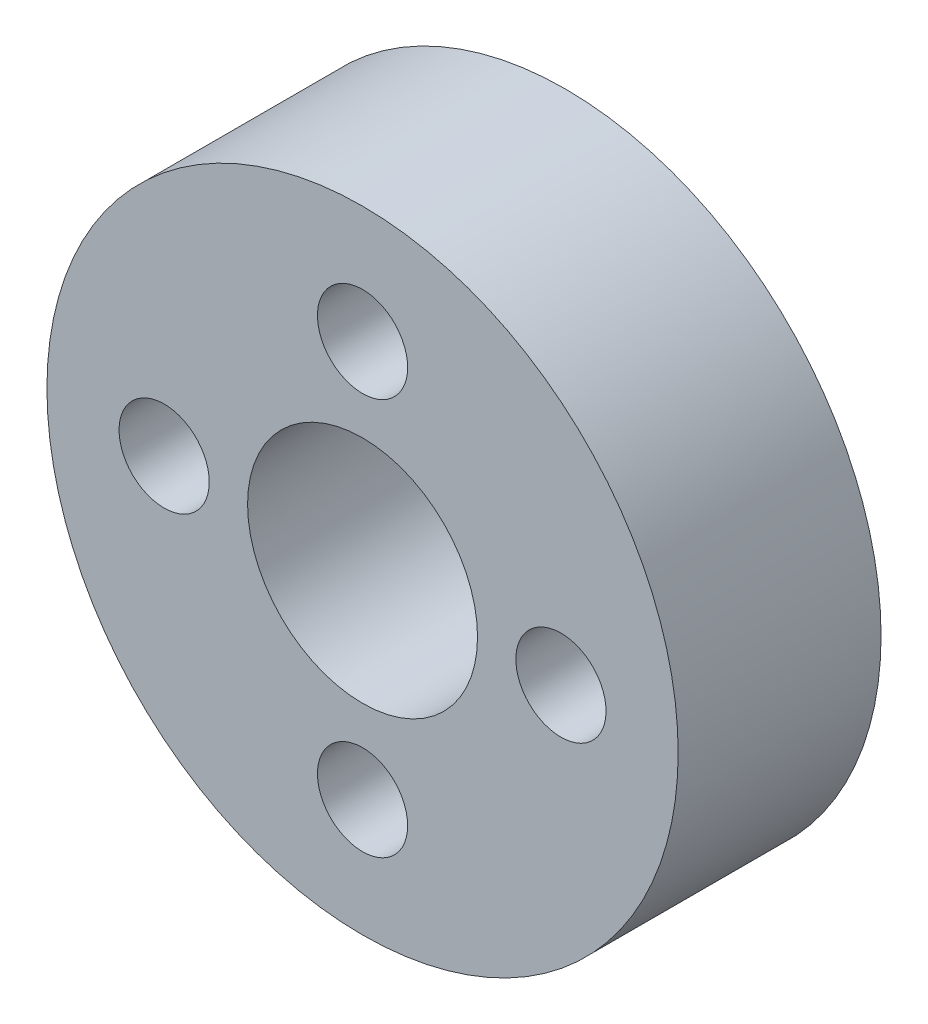
SolidWorks part; units mm, degrees
ref_plane "Front Plane" through (0, 0, 0) normal (0, 0, 1) x (1, 0, 0)
ref_plane "Top Plane" through (0, 0, 0) normal (0, 1, 0) x (1, 0, 0)
ref_plane "Right Plane" through (0, 0, 0) normal (1, 0, 0) x (0, 0, -1)
sketch "Sketch1" plane through (0, 0, 0) normal (0, 0, 1) x (1, 0, 0)
  line L0 (0, 11.176) -> (0, 0) construction
  line L5 (0, 0) -> (11.176, 0) construction
  line L6 (0, -11.176) -> (0, 0) construction
  line L7 (0, 0) -> (-11.176, 0) construction
  circle A0 centre (0, 0) radius 17.78
  circle A1 centre (-11.176, 0) radius 2.54
  circle A2 centre (0, -11.176) radius 2.54
  circle A3 centre (11.176, 0) radius 2.54
  circle A4 centre (0, 11.176) radius 2.54
  circle A5 centre (0, 0) radius 6.477
  dimension "D1" = 35.56
  dimension "D4" = 5.08
  dimension "D2" = 12.954
  dimension "D3" = 11.176
extrude "Boss-Extrude1" add sketch "Sketch1" along normal blind 11.43
sketch "Sketch2" plane through (0, 0, 0) normal (0, 0, -1) x (-1, 0, 0)
  line L1 (-8.255, -8.255) -> (8.255, -8.255)
  line L2 (-8.255, -8.255) -> (-8.255, 8.255)
  line L3 (-8.255, 8.255) -> (8.255, 8.255)
  line L4 (8.255, -8.255) -> (8.255, 8.255)
  line L5 (-8.255, -8.255) -> (8.255, 8.255) construction
  line L6 (-8.255, 8.255) -> (8.255, -8.255) construction
  circle A0 centre (0, 0) radius 6.477 construction
  circle A1 centre (0, 0) radius 6.477
  point P0 (0, 0)
  dimension "D1" = 16.51
extrude "Boss-Extrude2" add sketch "Sketch2" along normal blind 3.175
